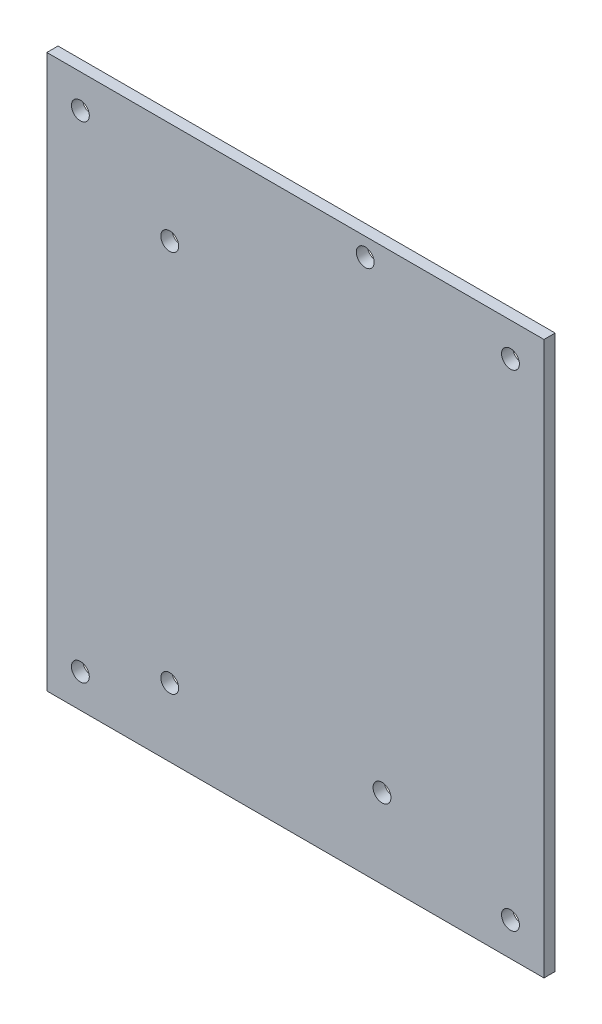
SolidWorks part; units mm, degrees
ref_plane "Front Plane" through (0, 0, 0) normal (0, 0, 1) x (1, 0, 0)
ref_plane "Top Plane" through (0, 0, 0) normal (0, 1, 0) x (1, 0, 0)
ref_plane "Right Plane" through (0, 0, 0) normal (1, 0, 0) x (0, 0, -1)
sketch "Sketch1" plane through (0, 0, 0) normal (0, 0, 1) x (1, 0, 0)
  line L1 (-37.8802, -33.0379) -> (51.1198, -33.0379)
  line L2 (-37.8802, -33.0379) -> (-37.8802, 65.9621)
  line L3 (-37.8802, 65.9621) -> (51.1198, 65.9621)
  line L4 (51.1198, -33.0379) -> (51.1198, 65.9621)
  dimension "D1" = 89
  dimension "D2" = 99
extrude "Boss-Extrude1" add sketch "Sketch1" along normal blind 2
sketch "Sketch2" plane through (0, 0, 2) normal (0, 0, 1) x (1, 0, 0)
  line L0 (-37.8802, 65.9621) -> (-37.8802, -33.0379) construction
  line L1 (51.1198, 65.9621) -> (-37.8802, 65.9621) construction
  line L2 (51.1198, -33.0379) -> (51.1198, 65.9621) construction
  line L3 (-37.8802, -33.0379) -> (51.1198, -33.0379) construction
  circle A0 centre (-31.8802, 59.9621) radius 1.6
  circle A1 centre (45.1198, 59.9621) radius 1.6
  circle A2 centre (-31.8802, -27.0379) radius 1.6
  circle A3 centre (45.1198, -27.0379) radius 1.6
  dimension "D1" = 3.2
  dimension "D4" = 3.2
  dimension "D7" = 3.2
  dimension "D10" = 3.2
  dimension "D2" = 6
  dimension "D3" = 6
  dimension "D5" = 6
  dimension "D6" = 6
  dimension "D8" = 6
  dimension "D9" = 6
  dimension "D11" = 6
  dimension "D12" = 6
extrude "Cut-Extrude1" cut sketch "Sketch2" against normal through all
sketch "Sketch3" plane through (0, 0, 2) normal (0, 0, 1) x (1, 0, 0)
  circle A0 centre (-15.8802, 47.7121) radius 1.6
  circle A1 centre (-31.8802, 59.9621) radius 1.6 construction
  circle A2 centre (-15.8802, -20.7879) radius 1.6
  circle A3 centre (-31.8802, -27.0379) radius 1.6 construction
  circle A4 centre (19.1198, 62.7121) radius 1.6
  circle A5 centre (45.1198, 59.9621) radius 1.6 construction
  circle A6 centre (22.1198, -18.7879) radius 1.6
  circle A7 centre (45.1198, -27.0379) radius 1.6 construction
  dimension "D1" = 3.2
  dimension "D2" = 16
  dimension "D4" = 3.2
  dimension "D5" = 16
  dimension "D6" = 6.25
  dimension "D7" = 3.2
  dimension "D8" = 26
  dimension "D9" = 2.75
  dimension "D10" = 3.2
  dimension "D11" = 23
  dimension "D12" = 8.25
  dimension "D3" = 12.25
extrude "Cut-Extrude2" cut sketch "Sketch3" against normal through all
